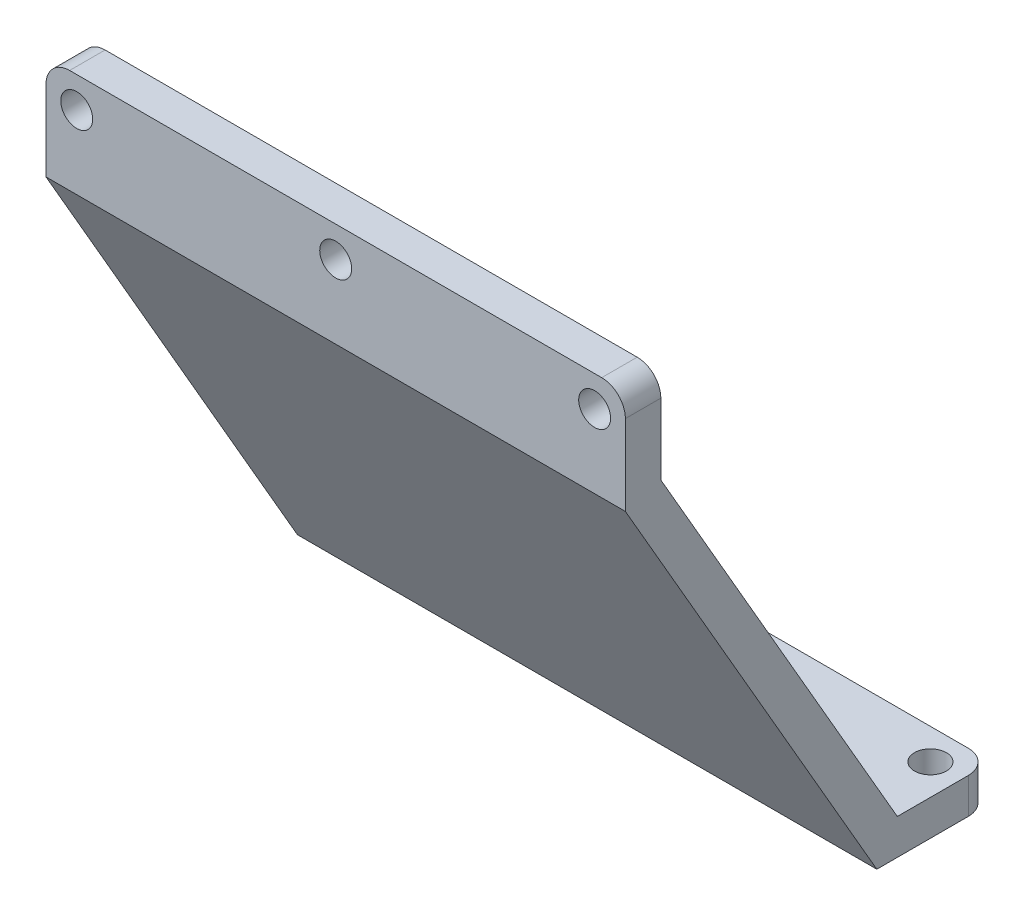
SolidWorks part; units mm, degrees
ref_plane "Plano frontal" through (0, 0, 0) normal (0, 0, 1) x (1, 0, 0)
ref_plane "Plano superior" through (0, 0, 0) normal (0, 1, 0) x (1, 0, 0)
ref_plane "Plano direito" through (0, 0, 0) normal (1, 0, 0) x (0, 0, -1)
sketch "Esboço1" plane through (0, 0, 0) normal (0, 0, 1) x (1, 0, 0)
  line L1 (-24.5, 22.82) -> (24.5, 22.82)
  line L2 (-24.5, 22.82) -> (-24.5, -22.82)
  line L3 (-24.5, -22.82) -> (24.5, -22.82)
  line L4 (24.5, 22.82) -> (24.5, -22.82)
  line L5 (-24.5, 22.82) -> (24.5, -22.82) construction
  line L6 (-24.5, -22.82) -> (24.5, 22.82) construction
  point P0 (0, 0)
  dimension "D1" = 49
  dimension "D2" = 45.64
extrude "Ressalto-extrusão1" add sketch "Esboço1" along normal blind 31
sketch "Esboço2" plane through (-24.5, 0, 0) normal (-1, 0, 0) x (0, 0, 1)
  line L5 (9.7326, -22.82) -> (31, -22.82)
  line L6 (31, -22.82) -> (31, 14.0223)
  line L8 (9.7326, -22.82) -> (31, 14.0223)
  dimension "D1" = 42.54
extrude "Corte-extrusão1" cut sketch "Esboço2" against normal through all
sketch "Esboço3" plane through (-24.5, 0, 0) normal (-1, 0, 0) x (0, 0, 1)
  line L1 (0, 22.82) -> (0, -22.82) construction
  line L2 (0, -19.82) -> (8, -19.82)
  line L4 (31, 22.82) -> (0, 22.82) construction
  line L5 (28, 22.82) -> (28, 14.82)
  line L6 (8, -19.82) -> (28, 14.82)
  line L7 (0, -19.82) -> (0, 22.82)
  line L8 (0, 22.82) -> (28, 22.82)
extrude "Corte-extrusão2" cut sketch "Esboço3" against normal through all
sketch "Esboço5" plane through (0, -19.82, 0) normal (0, 1, 0) x (1, 0, 0)
  line L0 (24.5, 0) -> (24.5, -8) construction
  line L1 (24.5, 0) -> (-24.5, 0) construction
  line L2 (-24.5, 0) -> (-24.5, -8) construction
  circle A0 centre (21.9, -2.6) radius 1.35
  circle A1 centre (0, -2.6) radius 1.35
  circle A2 centre (-21.9, -2.6) radius 1.35
  dimension "D7" = 2.7
  dimension "D8" = 2.7
  dimension "D9" = 2.7
  dimension "D1" = 2.6
  dimension "D2" = 2.6
  dimension "D3" = 2.6
  dimension "D4" = 24.5
  dimension "D5" = 2.6
  dimension "D6" = 2.6
extrude "Corte-extrusão4" cut sketch "Esboço5" against normal through all
sketch "Esboço6" plane through (0, 0, 28) normal (0, 0, -1) x (-1, 0, 0)
  line L0 (24.5, 14.82) -> (24.5, 22.82) construction
  line L1 (-24.5, 14.82) -> (-24.5, 22.82) construction
  line L2 (-24.5, 22.82) -> (24.5, 22.82) construction
  circle A0 centre (21.9, 20.22) radius 1.35
  circle A1 centre (0, 20.22) radius 1.35
  circle A2 centre (-21.9, 20.22) radius 1.35
  dimension "D7" = 2.7
  dimension "D8" = 2.7
  dimension "D9" = 2.7
  dimension "D1" = 2.6
  dimension "D2" = 2.6
  dimension "D3" = 24.5
  dimension "D4" = 2.6
  dimension "D5" = 2.6
  dimension "D6" = 2.6
extrude "Corte-extrusão5" cut sketch "Esboço6" against normal through all
fillet "Filete1" radius 2 4 edges at (24.5, 22.82, 29.5) (-24.5, 22.82, 29.5) (-24.5, -21.32, 0) (24.5, -21.32, 0)
